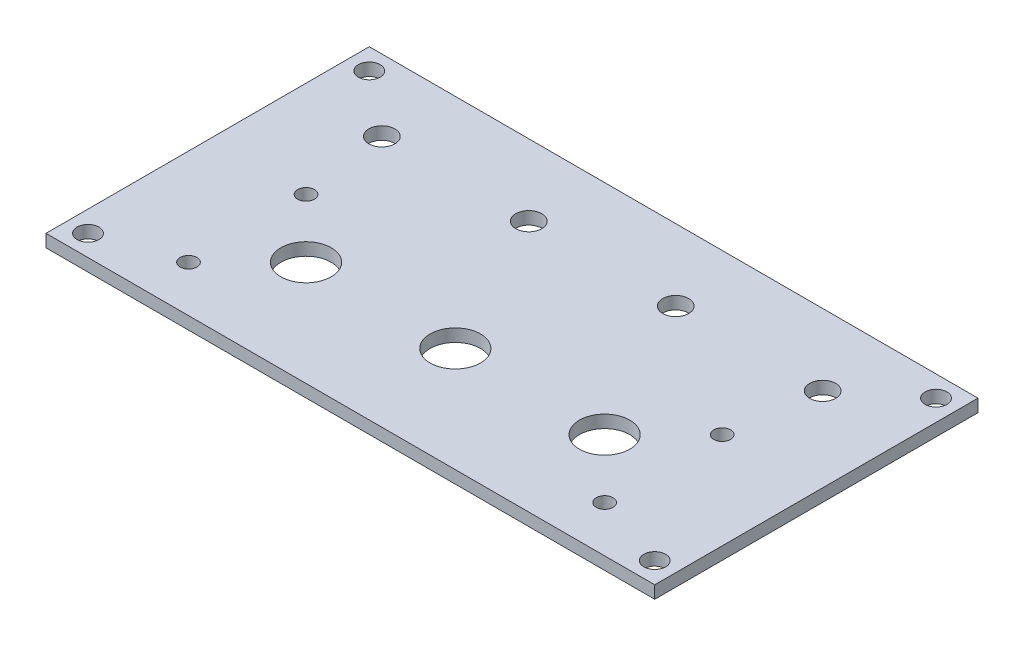
SolidWorks part; units mm, degrees
ref_plane "Front Plane" through (0, 0, 0) normal (0, 0, 1) x (1, 0, 0)
ref_plane "Top Plane" through (0, 0, 0) normal (0, 1, 0) x (1, 0, 0)
ref_plane "Right Plane" through (0, 0, 0) normal (1, 0, 0) x (0, 0, -1)
sketch "Sketch1" plane through (0, 0, 0) normal (0, 1, 0) x (1, 0, 0)
  line L1 (0, 0) -> (145, 0)
  line L2 (0, 0) -> (0, 77)
  line L3 (0, 77) -> (145, 77)
  line L4 (145, 0) -> (145, 77)
  line L5 (12.5, 47) -> (27.5, 47)
  line L6 (12.5, 47) -> (12.5, 56)
  line L7 (12.5, 56) -> (27.5, 56)
  line L8 (27.5, 47) -> (27.5, 56)
  circle A0 centre (20, 60) radius 3.1
  circle A1 centre (55, 60) radius 3.1
  circle A2 centre (90, 60) radius 3.1
  circle A3 centre (125, 60) radius 3.1
  circle A4 centre (5, 72) radius 2.6
  circle A5 centre (5, 5) radius 2.6
  circle A6 centre (140, 5) radius 2.6
  circle A7 centre (140, 72) radius 2.6
  circle A8 centre (20, 60) radius 8.5
  circle A9 centre (55, 60) radius 8.5
  circle A10 centre (90, 60) radius 8.5
  circle A11 centre (125, 60) radius 8.5
  circle A12 centre (36.94, 25) radius 6
  circle A13 centre (72.5, 25) radius 6
  circle A14 centre (108.06, 25) radius 6
  circle A15 centre (22.94, 39) radius 2
  circle A16 centre (122.06, 39) radius 2
  circle A17 centre (122.06, 11) radius 2
  circle A18 centre (22.94, 11) radius 2
  dimension "D1" = 6.2
  dimension "D2" = 6.2
  dimension "D3" = 6.2
  dimension "D4" = 6.2
  dimension "D5" = 5.2
  dimension "D6" = 5.2
  dimension "D7" = 5.2
  dimension "D8" = 5.2
  dimension "D17" = 17
  dimension "D21" = 17
  dimension "D22" = 17
  dimension "D23" = 17
  dimension "D24" = 12
  dimension "D25" = 12
  dimension "D26" = 12
  dimension "D46" = 4
  dimension "D47" = 4
  dimension "D48" = 4
  dimension "D49" = 4
  dimension "D9" = 5
  dimension "D10" = 5
  dimension "D11" = 5
  dimension "D12" = 5
  dimension "D13" = 5
  dimension "D14" = 5
  dimension "D15" = 5
  dimension "D16" = 5
  dimension "D18" = 13
  dimension "D19" = 15
  dimension "D20" = 7.5
  dimension "D27" = 17
  dimension "D28" = 20
  dimension "D29" = 35
  dimension "D30" = 17
  dimension "D31" = 35
  dimension "D32" = 17
  dimension "D33" = 35
  dimension "D34" = 17
  dimension "D35" = 35
  dimension "D36" = 77
  dimension "D37" = 35.56
  dimension "D38" = 35.56
  dimension "D39" = 36.94
  dimension "D40" = 25
  dimension "D41" = 14
  dimension "D42" = 20
  dimension "D43" = 14
  dimension "D44" = 14
  dimension "D45" = 14
  dimension "D50" = 14
  dimension "D51" = 14
  dimension "D52" = 14
  dimension "D53" = 14
extrude "Boss-Extrude1" add sketch "Sketch1" along normal blind 3 contours L1 L4 L3 L2 A14 A13 A12 A11 A10 A9 A8 L8 L5 L6 A7 A6 A5 A4 | A8 L6 L5 L8 | L7 A8 | L7 A8 A0 | A9 A1 | A10 A2 | A11 A3
